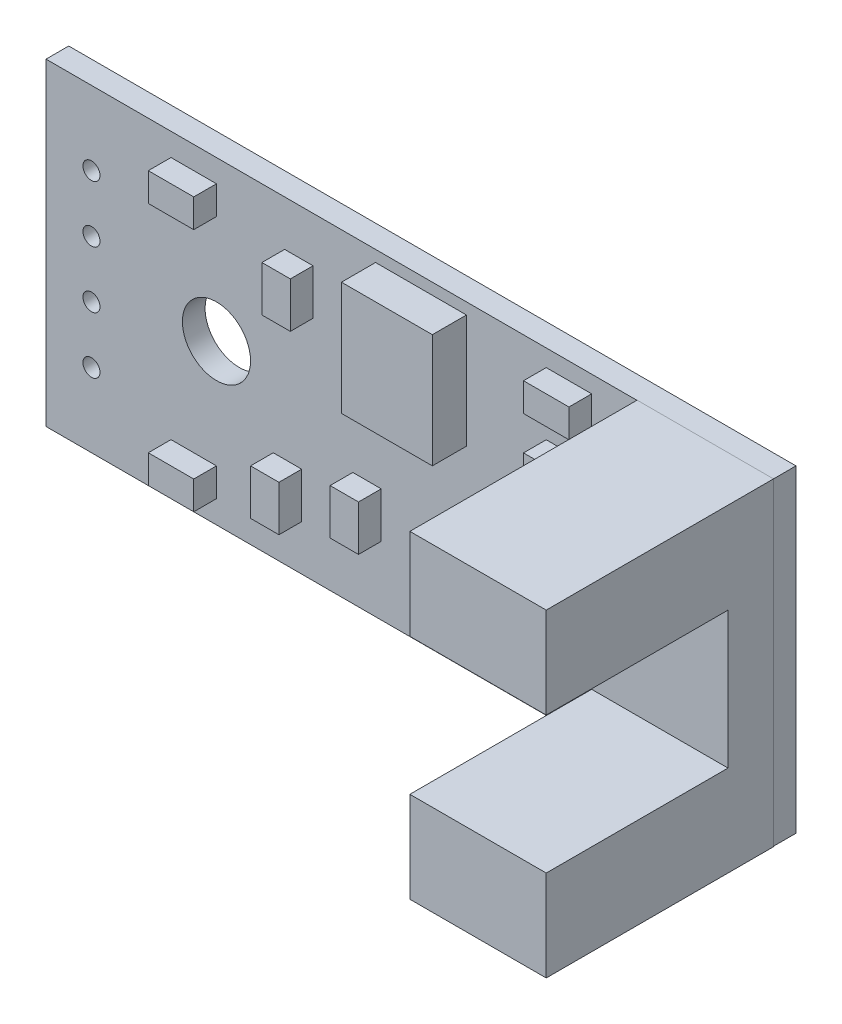
SolidWorks part; units mm, degrees
ref_plane "Plan de face" through (0, 0, 0) normal (0, 0, 1) x (1, 0, 0)
ref_plane "Plan de dessus" through (0, 0, 0) normal (0, 1, 0) x (1, 0, 0)
ref_plane "Plan de droite" through (0, 0, 0) normal (1, 0, 0) x (0, 0, -1)
sketch "Esquisse1" plane through (0, 0, 0) normal (0, 0, 1) x (1, 0, 0)
  line L0 (2, 14) -> (2, 10.75) construction
  line L5 (32, 14) -> (0, 14)
  line L6 (32, 14) -> (32, 0)
  line L7 (32, 0) -> (0, 0)
  line L8 (0, 14) -> (0, 0)
  line L9 (2, 10.75) -> (2, 8.25) construction
  line L10 (2, 8.25) -> (2, 5.75) construction
  line L11 (2, 5.75) -> (2, 3.25) construction
  line L12 (2, 3.25) -> (2, 0) construction
  circle A3 centre (2, 8.25) radius 0.375
  circle A4 centre (2, 10.75) radius 0.375
  circle A5 centre (2, 5.75) radius 0.375
  circle A6 centre (2, 3.25) radius 0.375
  circle A7 centre (7.5, 7) radius 1.5
  dimension "D1" = 14
  dimension "D2" = 32
  dimension "D3" = 0.75
  dimension "D6" = 3
  dimension "D7" = 7
  dimension "D8" = 7.5
  dimension "D4" = 2.5
  dimension "D5" = 2
extrude "Boss.-Extru.1" add sketch "Esquisse1" along normal blind 1
sketch "Esquisse2" plane through (0, 0, 1) normal (0, 0, 1) x (1, 0, 0)
  line L1 (32.01, 14.01) -> (26.01, 14.01)
  line L2 (32.01, 14.01) -> (32.01, -0.01)
  line L3 (32.01, -0.01) -> (26.01, -0.01)
  line L4 (26.01, 14.01) -> (26.01, -0.01)
  line L5 (0, 0) -> (32, 0) construction
  line L6 (32, 14) -> (0, 14) construction
  line L7 (32, 0) -> (32, 14) construction
  dimension "D1" = 6
  dimension "D2" = 0.01
  dimension "D3" = 0.01
  dimension "D4" = 0.01
extrude "Boss.-Extru.2" add sketch "Esquisse2" along normal blind 2
sketch "Esquisse3" plane through (0, 0, 3) normal (0, 0, 1) x (1, 0, 0)
  line L0 (32.01, -0.01) -> (32.01, 14.01) construction
  line L1 (26.01, 14.01) -> (32.01, 14.01)
  line L2 (26.01, 14.01) -> (26.01, 10.01)
  line L3 (26.01, 10.01) -> (32.01, 10.01)
  line L4 (32.01, 14.01) -> (32.01, 10.01)
  line L5 (26.01, -0.01) -> (32.01, -0.01) construction
  line L6 (26.01, -0.01) -> (32.01, -0.01)
  line L7 (26.01, -0.01) -> (26.01, 3.99)
  line L8 (26.01, 3.99) -> (32.01, 3.99)
  line L9 (32.01, -0.01) -> (32.01, 3.99)
  line L10 (26.01, 14.01) -> (26.01, -0.01) construction
  dimension "D1" = 4
  dimension "D2" = 4
extrude "Boss.-Extru.3" add sketch "Esquisse3" along normal blind 8
sketch "Esquisse4" plane through (0, 0, 1) normal (0, 0, 1) x (1, 0, 0)
  line L0 (26.01, 14) -> (0, 14) construction
  line L1 (14.5, 13.5) -> (18.5, 13.5)
  line L2 (14.5, 13.5) -> (14.5, 8.5)
  line L3 (14.5, 8.5) -> (18.5, 8.5)
  line L4 (18.5, 13.5) -> (18.5, 8.5)
  line L5 (0, 14) -> (0, 0) construction
  dimension "D1" = 4
  dimension "D2" = 5
  dimension "D3" = 0.5
  dimension "D4" = 14.5
extrude "Boss.-Extru.4" add sketch "Esquisse4" along normal blind 1.5
sketch "Esquisse5" plane through (0, 0, 1) normal (0, 0, 1) x (1, 0, 0)
  line L0 (26.01, 14) -> (0, 14) construction
  line L1 (10.5, 12) -> (11.75, 12)
  line L2 (10.5, 12) -> (10.5, 10)
  line L3 (10.5, 10) -> (11.75, 10)
  line L4 (11.75, 12) -> (11.75, 10)
  line L5 (10, 4) -> (11.25, 4)
  line L6 (10, 4) -> (10, 2)
  line L7 (10, 2) -> (11.25, 2)
  line L8 (11.25, 4) -> (11.25, 2)
  line L9 (13.5, 5) -> (14.75, 5)
  line L10 (13.5, 5) -> (13.5, 3)
  line L11 (13.5, 3) -> (14.75, 3)
  line L12 (14.75, 5) -> (14.75, 3)
  line L13 (17.25, 5) -> (18.5, 5)
  line L14 (17.25, 5) -> (17.25, 3)
  line L15 (17.25, 3) -> (18.5, 3)
  line L16 (18.5, 5) -> (18.5, 3)
  line L17 (22.01, 13.25) -> (24.01, 13.25)
  line L18 (22.01, 13.25) -> (22.01, 12)
  line L19 (22.01, 12) -> (24.01, 12)
  line L20 (24.01, 13.25) -> (24.01, 12)
  line L21 (22.01, 10.5) -> (24.01, 10.5)
  line L22 (22.01, 10.5) -> (22.01, 9.25)
  line L23 (22.01, 9.25) -> (24.01, 9.25)
  line L24 (24.01, 10.5) -> (24.01, 9.25)
  line L25 (22.01, 7.75) -> (24.01, 7.75)
  line L26 (22.01, 7.75) -> (22.01, 6.5)
  line L27 (22.01, 6.5) -> (24.01, 6.5)
  line L28 (24.01, 7.75) -> (24.01, 6.5)
  line L29 (22.01, 5) -> (24.01, 5)
  line L30 (22.01, 5) -> (22.01, 3.75)
  line L31 (22.01, 3.75) -> (24.01, 3.75)
  line L32 (24.01, 5) -> (24.01, 3.75)
  line L33 (22.01, 2.25) -> (24.01, 2.25)
  line L34 (22.01, 2.25) -> (22.01, 1)
  line L35 (22.01, 1) -> (24.01, 1)
  line L36 (24.01, 2.25) -> (24.01, 1)
  line L37 (7.5, 13) -> (5.5, 13)
  line L38 (7.5, 13) -> (7.5, 11.75)
  line L39 (7.5, 11.75) -> (5.5, 11.75)
  line L40 (5.5, 13) -> (5.5, 11.75)
  line L41 (7.5, 2.25) -> (5.5, 2.25)
  line L42 (7.5, 2.25) -> (7.5, 1)
  line L43 (7.5, 1) -> (5.5, 1)
  line L44 (5.5, 2.25) -> (5.5, 1)
  line L45 (0, 0) -> (26.01, 0) construction
  line L46 (0, 14) -> (0, 0) construction
  line L47 (26.01, 14) -> (26.01, 0) construction
  dimension "D1" = 2
  dimension "D2" = 1.25
  dimension "D3" = 1
  dimension "D4" = 1
  dimension "D5" = 5.5
  dimension "D6" = 5.5
  dimension "D7" = 2
  dimension "D8" = 10.5
  dimension "D9" = 10
  dimension "D10" = 2
  dimension "D11" = 3
  dimension "D12" = 3
  dimension "D13" = 2.5
  dimension "D14" = 13.5
  dimension "D15" = 1.5
  dimension "D16" = 1.5
  dimension "D17" = 1.5
  dimension "D18" = 1.5
  dimension "D19" = 1
  dimension "D20" = 2
extrude "Boss.-Extru.5" add sketch "Esquisse5" along normal blind 1
